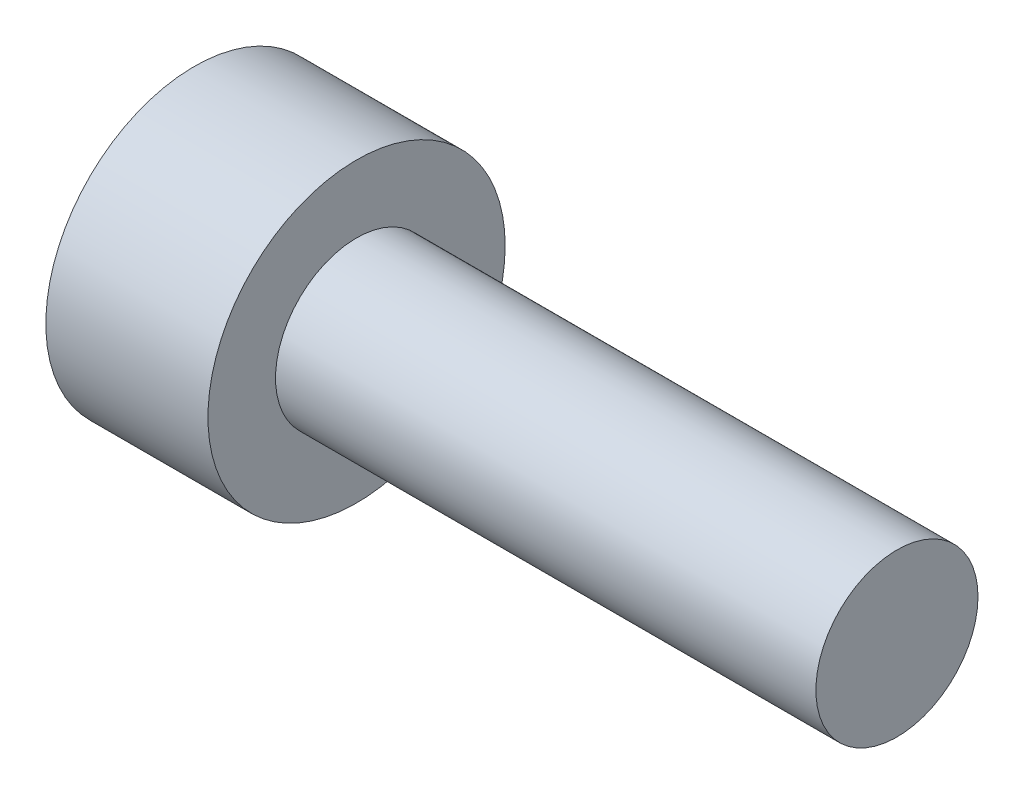
SolidWorks part; units mm, degrees
material "1.4000 (X6Cr13)"
ref_plane "Ebene vorne" through (0, 0, 0) normal (1, 0, 0) x (0, 1, 0)
ref_plane "Ebene oben" through (0, 0, 0) normal (0, 0, 1) x (0, 1, 0)
ref_plane "Ebene rechts" through (0, 0, 0) normal (0, 1, 0) x (-1, 0, 0)
sketch "Skizze1" plane through (0, 0, 0) normal (1, 0, 0) x (0, 1, 0)
  circle A0 centre (0, 0) radius 2.75
extrude "Aufsatz-Linear austragen1" add sketch "Skizze1" along normal blind 3 contours A0
sketch "Skizze2" plane through (0, 0, 0) normal (1, 0, 0) x (0, 1, 0)
  circle A0 centre (0, 0) radius 1.5
extrude "Aufsatz-Linear austragen2" add sketch "Skizze2" along normal blind 10 from offset 3
